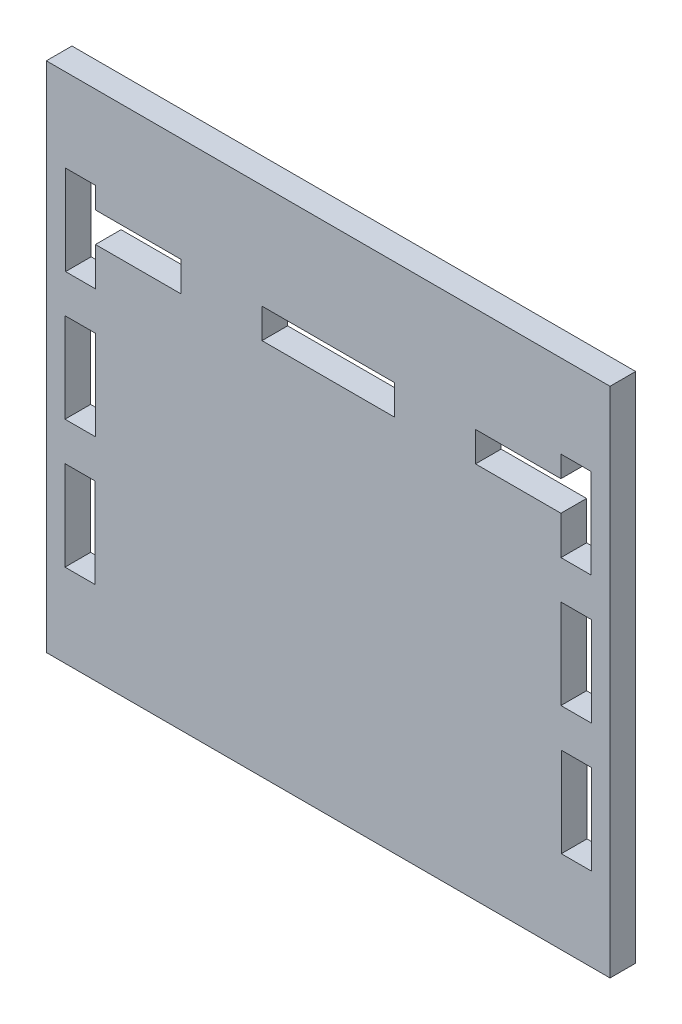
SolidWorks part; units mm, degrees
ref_plane "Спереди" through (0, 0, 0) normal (0, 0, 1) x (1, 0, 0)
ref_plane "Сверху" through (0, 0, 0) normal (0, 1, 0) x (1, 0, 0)
ref_plane "Справа" through (0, 0, 0) normal (1, 0, 0) x (0, 0, -1)
sketch "Эскиз1" plane through (0, 0, 0) normal (0, 0, 1) x (1, 0, 0)
  line L0 (0, 14.5) -> (0, 22.8101) construction
  line L1 (-7.75, 17.75) -> (7.75, 17.75)
  line L2 (-7.75, 17.75) -> (-7.75, 14.25)
  line L3 (-7.75, 14.25) -> (7.75, 14.25)
  line L4 (-17.25, 17.75) -> (-27.25, 17.75)
  line L5 (-17.25, 17.75) -> (-17.25, 14.25)
  line L6 (-17.25, 14.25) -> (-27.25, 14.25)
  line L7 (-27.25, 14.25) -> (-27.25, 9.75)
  line L8 (-30.75, 20.25) -> (-27.25, 20.25)
  line L9 (-30.75, 20.25) -> (-30.75, 9.75)
  line L10 (-30.75, 9.75) -> (-27.25, 9.75)
  line L11 (-27.25, 20.25) -> (-27.25, 17.75)
  line L12 (-30.8168, 5.25) -> (-27.25, 5.25)
  line L13 (-30.8168, 5.25) -> (-30.8168, -5.25)
  line L14 (-30.8168, -5.25) -> (-27.25, -5.25)
  line L15 (-27.25, 5.25) -> (-27.25, -5.25)
  line L16 (-30.8168, -9.75) -> (-27.2966, -9.75)
  line L17 (-30.8168, -9.75) -> (-30.8168, -20.25)
  line L18 (-30.8168, -20.25) -> (-27.2966, -20.25)
  line L19 (-27.2966, -9.75) -> (-27.2966, -20.25)
  line L20 (-33, 30) -> (33, 30)
  line L21 (-33, 30) -> (-33, -30)
  line L22 (-33, -30) -> (33, -30)
  line L23 (33, 30) -> (33, -30)
  line L24 (27.2966, -9.75) -> (27.2966, -20.25)
  line L25 (30.8168, -20.25) -> (27.2966, -20.25)
  line L26 (30.8168, -9.75) -> (30.8168, -20.25)
  line L27 (30.8168, -9.75) -> (27.2966, -9.75)
  line L28 (27.25, 5.25) -> (27.25, -5.25)
  line L29 (30.8168, -5.25) -> (27.25, -5.25)
  line L30 (30.8168, 5.25) -> (30.8168, -5.25)
  line L31 (30.8168, 5.25) -> (27.25, 5.25)
  line L32 (27.25, 20.25) -> (27.25, 17.75)
  line L33 (30.75, 9.75) -> (27.25, 9.75)
  line L34 (30.75, 20.25) -> (30.75, 9.75)
  line L35 (30.75, 20.25) -> (27.25, 20.25)
  line L36 (27.25, 14.25) -> (27.25, 9.75)
  line L37 (17.25, 14.25) -> (27.25, 14.25)
  line L38 (17.25, 17.75) -> (17.25, 14.25)
  line L39 (17.25, 17.75) -> (27.25, 17.75)
  line L40 (7.75, 17.75) -> (7.75, 14.25)
  point P22 (-30.8168, -15)
  point P26 (0, -30)
  point P27 (0, 30)
  dimension "D1" = 3.5
  dimension "D2" = 3.5
  dimension "D3" = 9.5
  dimension "D4" = 0
  dimension "D5" = 10.5
  dimension "D6" = 2.5
  dimension "D7" = 10
  dimension "D8" = 10.5
  dimension "D9" = 4.5
  dimension "D10" = 0
  dimension "D11" = 4.5
  dimension "D12" = 10.5
  dimension "D13" = 0
  dimension "D14" = 60
extrude "Бобышка-Вытянуть1" add sketch "Эскиз1" along normal blind 3
